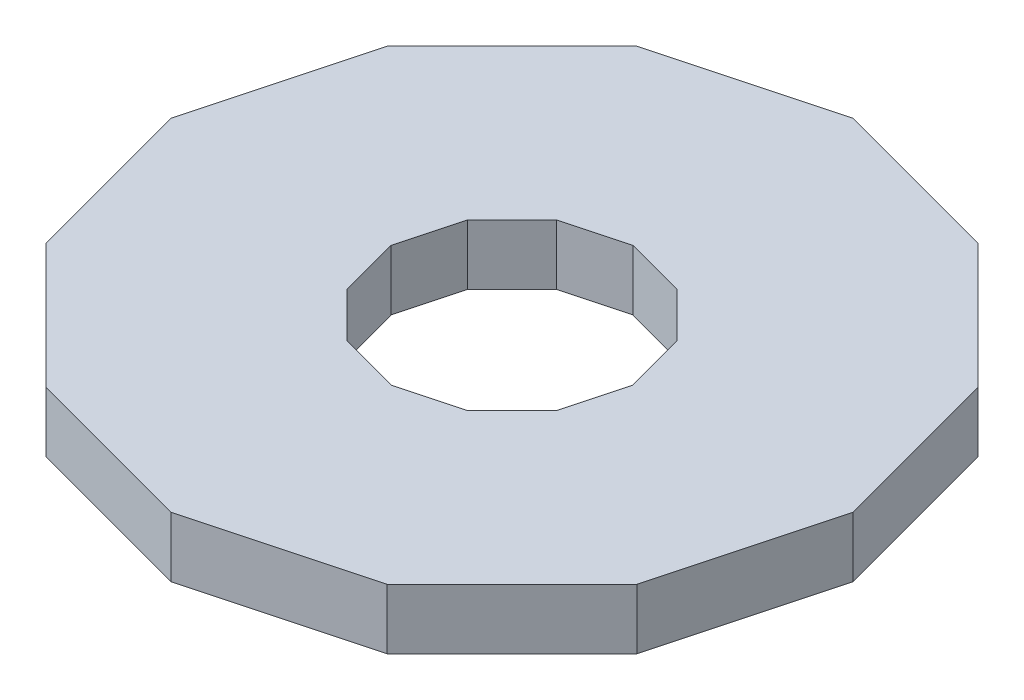
SolidWorks part; units mm, degrees
ref_plane "Front Plane" through (0, 0, 0) normal (0, 0, 1) x (1, 0, 0)
ref_plane "Top Plane" through (0, 0, 0) normal (0, 1, 0) x (1, 0, 0)
ref_plane "Right Plane" through (0, 0, 0) normal (1, 0, 0) x (0, 0, -1)
sketch "Sketch2" plane through (0, 0, 0) normal (0, 1, 0) x (1, 0, 0)
  line L0 (0, 0) -> (-38.2674, 0) construction
  line L1 (-107.9519, 0) -> (-93.4891, -53.9759)
  line L2 (-93.4891, -53.9759) -> (-53.9759, -93.4891)
  line L3 (-53.9759, -93.4891) -> (0, -107.9519)
  line L4 (0, -107.9519) -> (53.9759, -93.4891)
  line L5 (53.9759, -93.4891) -> (93.4891, -53.9759)
  line L6 (93.4891, -53.9759) -> (107.9519, 0)
  line L7 (107.9519, 0) -> (93.4891, 53.9759)
  line L8 (93.4891, 53.9759) -> (53.9759, 93.4891)
  line L9 (53.9759, 93.4891) -> (0, 107.9519)
  line L10 (0, 107.9519) -> (-53.9759, 93.4891)
  line L11 (-53.9759, 93.4891) -> (-93.4891, 53.9759)
  line L12 (-93.4891, 53.9759) -> (-107.9519, 0)
  line L13 (-38.2674, 0) -> (-33.1406, -19.1337)
  line L14 (-33.1406, -19.1337) -> (-19.1337, -33.1406)
  line L15 (-19.1337, -33.1406) -> (0, -38.2674)
  line L16 (0, -38.2674) -> (19.1337, -33.1406)
  line L17 (19.1337, -33.1406) -> (33.1406, -19.1337)
  line L18 (33.1406, -19.1337) -> (38.2674, 0)
  line L19 (38.2674, 0) -> (33.1406, 19.1337)
  line L20 (33.1406, 19.1337) -> (19.1337, 33.1406)
  line L21 (19.1337, 33.1406) -> (0, 38.2674)
  line L22 (0, 38.2674) -> (-19.1337, 33.1406)
  line L23 (-19.1337, 33.1406) -> (-33.1406, 19.1337)
  line L24 (-33.1406, 19.1337) -> (-38.2674, 0)
  line L25 (-107.9519, 0) -> (-38.2674, 0) construction
  circle A0 centre (0, 0) radius 104.2735 construction
  circle A1 centre (0, 0) radius 36.9635 construction
  dimension "D1" = 55.88
  dimension "D2" = 67.31
extrude "Boss-Extrude2" add sketch "Sketch2" along normal blind 19.05
